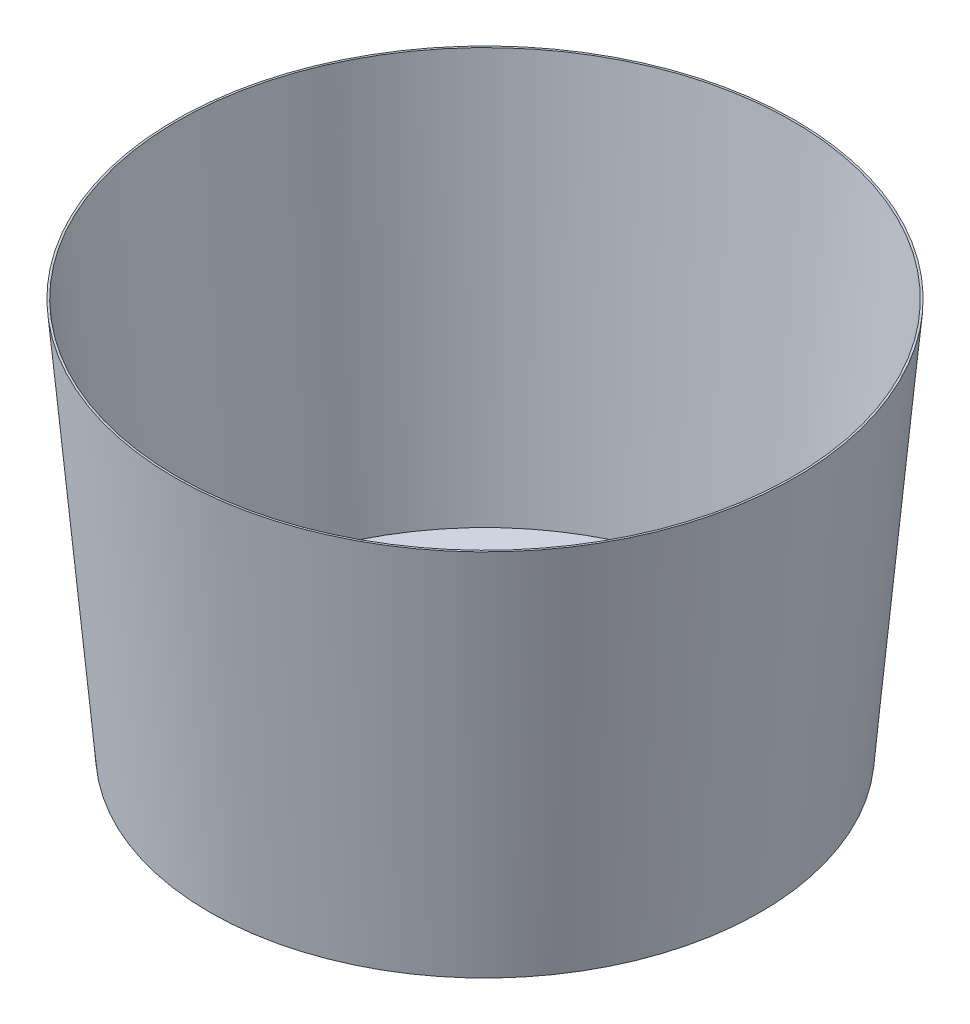
SolidWorks part; units mm, degrees
material "PET"
ref_plane "Front Plane" through (0, 0, 0) normal (0, 0, 1) x (1, 0, 0)
ref_plane "Top Plane" through (0, 0, 0) normal (0, 1, 0) x (1, 0, 0)
ref_plane "Right Plane" through (0, 0, 0) normal (1, 0, 0) x (0, 0, -1)
sketch "Sketch1" plane through (0, 0, 0) normal (0, 1, 0) x (1, 0, 0)
  circle A0 centre (0, 0) radius 35.56
  dimension "D1" = 71.12
extrude "Boss-Extrude1" add sketch "Sketch1" along normal blind 50.8 draft 5 draft outward yes
sketch "Sketch2" plane through (0, 50.8, 0) normal (0, 1, 0) x (1, 0, 0)
  circle A0 centre (0, 0) radius 39.7504
  circle A1 centre (0, 0) radius 40.0044 construction
  dimension "D1" = 0.254
extrude "Cut-Extrude1" cut sketch "Sketch2" against normal offset from surface 0.254 draft 5
